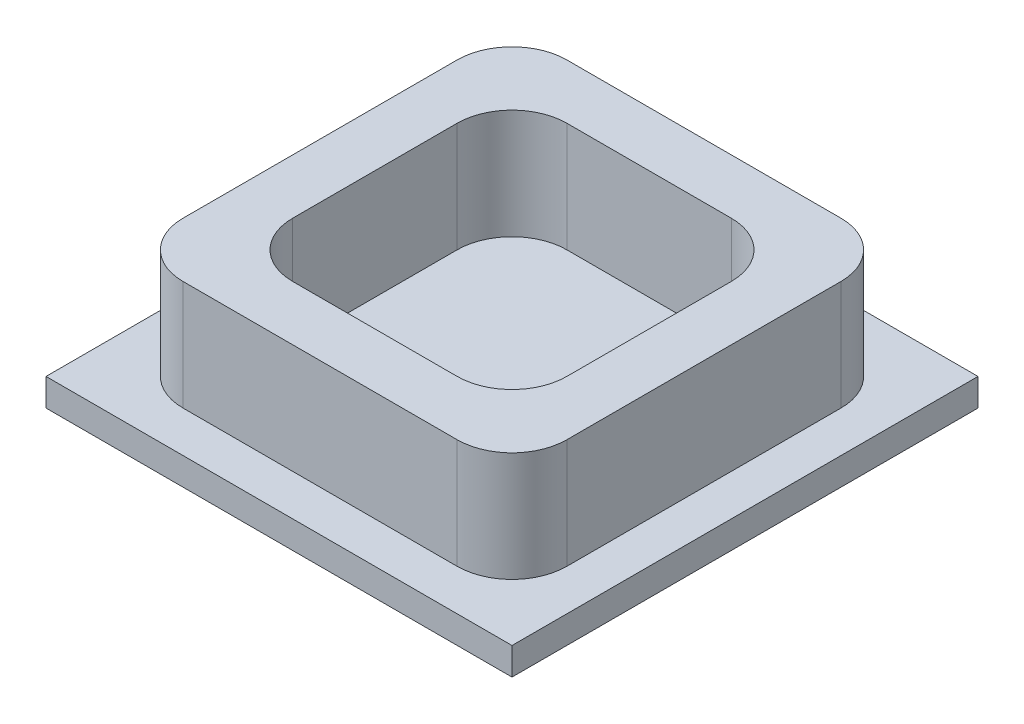
SolidWorks part; units mm, degrees
ref_plane "Front Plane" through (0, 0, 0) normal (0, 0, 1) x (1, 0, 0)
ref_plane "Top Plane" through (0, 0, 0) normal (0, 1, 0) x (1, 0, 0)
ref_plane "Right Plane" through (0, 0, 0) normal (1, 0, 0) x (0, 0, -1)
sketch "Sketch1" plane through (0, 0, 0) normal (0, 1, 0) x (1, 0, 0)
  line L1 (8.5, -8.5) -> (-8.5, -8.5)
  line L2 (8.5, -8.5) -> (8.5, 8.5)
  line L3 (8.5, 8.5) -> (-8.5, 8.5)
  line L4 (-8.5, -8.5) -> (-8.5, 8.5)
  line L5 (8.5, -8.5) -> (-8.5, 8.5) construction
  line L6 (8.5, 8.5) -> (-8.5, -8.5) construction
  point P0 (0, 0)
  dimension "D1" = 17
  dimension "D2" = 17
extrude "Boss-Extrude1" add sketch "Sketch1" along normal blind 1
sketch "Sketch2" plane through (0, 1, 0) normal (0, 1, 0) x (1, 0, 0)
  line L0 (-8.5, 8.5) -> (-8.5, -8.5) construction
  line L1 (-7, 7) -> (7, 7)
  line L2 (-7, 7) -> (-7, -7)
  line L3 (-7, -7) -> (7, -7)
  line L4 (7, 7) -> (7, -7)
  line L5 (-7, 7) -> (7, -7) construction
  line L6 (-7, -7) -> (7, 7) construction
  line L7 (8.5, 8.5) -> (-8.5, 8.5) construction
  line L8 (-5, 5) -> (-5, -5)
  line L9 (-5, -5) -> (5, -5)
  line L10 (5, 5) -> (5, -5)
  line L11 (-5, 5) -> (5, 5)
  point P0 (0, 0)
  dimension "D1" = 1.5
  dimension "D2" = 1.5
  dimension "D3" = 2
extrude "Boss-Extrude2" add sketch "Sketch2" along normal blind 4
fillet "Fillet1" radius 2 8 edges at (-5, 3, 5) (5, 3, 5) (5, 3, -5) (-5, 3, -5) (-7, 3, 7) (7, 3, 7) (7, 3, -7) (-7, 3, -7)
